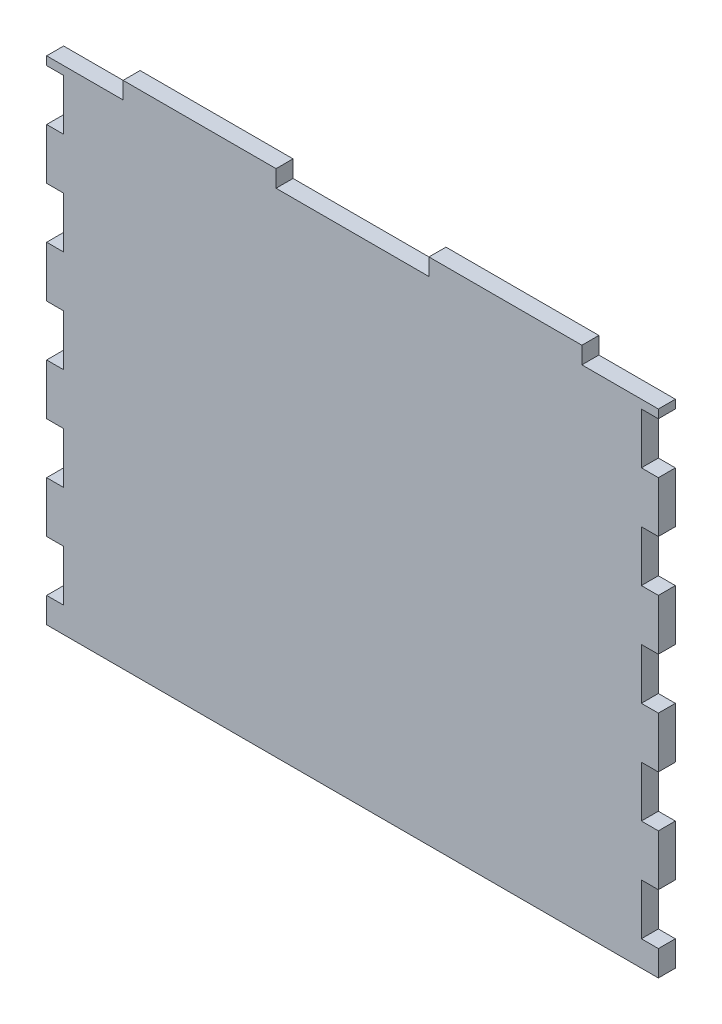
SolidWorks part; units mm, degrees
ref_plane "Front Plane" through (0, 0, 0) normal (0, 0, 1) x (1, 0, 0)
ref_plane "Top Plane" through (0, 0, 0) normal (0, 1, 0) x (1, 0, 0)
ref_plane "Right Plane" through (0, 0, 0) normal (1, 0, 0) x (0, 0, -1)
sketch "Sketch1" plane through (0, 0, 0) normal (0, 0, 1) x (1, 0, 0)
  line L0 (85.725, 100.551) -> (114.3, 100.551) construction
  line L1 (85.725, 95.25) -> (28.575, 95.25)
  line L2 (114.3, 88.9) -> (114.3, 85.725)
  line L3 (114.3, -95.25) -> (-114.3, -95.25)
  line L4 (-114.3, 88.9) -> (-114.3, 85.725)
  line L5 (114.3, 95.25) -> (-114.3, -95.25) construction
  line L6 (114.3, -95.25) -> (-114.3, 95.25) construction
  line L7 (85.725, 95.25) -> (85.725, 88.9)
  line L8 (28.575, 95.25) -> (28.575, 88.9)
  line L9 (-28.575, 95.25) -> (-28.575, 88.9)
  line L10 (-85.725, 95.25) -> (-85.725, 88.9)
  line L11 (-85.725, 88.9) -> (-114.3, 88.9)
  line L12 (-28.575, 88.9) -> (28.575, 88.9)
  line L13 (85.725, 88.9) -> (114.3, 88.9)
  line L14 (-28.575, 95.25) -> (-85.725, 95.25)
  line L15 (124.9833, 95.25) -> (124.9833, 85.725) construction
  line L16 (114.3, 85.725) -> (107.95, 85.725)
  line L17 (114.3, 66.675) -> (107.95, 66.675)
  line L18 (114.3, 47.625) -> (107.95, 47.625)
  line L19 (114.3, 28.575) -> (107.95, 28.575)
  line L20 (114.3, 9.525) -> (107.95, 9.525)
  line L21 (114.3, -9.525) -> (107.95, -9.525)
  line L22 (114.3, -28.575) -> (107.95, -28.575)
  line L23 (114.3, -47.625) -> (107.95, -47.625)
  line L24 (114.3, -66.675) -> (107.95, -66.675)
  line L25 (114.3, -85.725) -> (107.95, -85.725)
  line L26 (107.95, -9.525) -> (107.95, 9.525)
  line L27 (107.95, -85.725) -> (107.95, -66.675)
  line L28 (0, 49.4398) -> (0, -43.8374) construction
  line L29 (-114.3, -85.725) -> (-107.95, -85.725)
  line L30 (-114.3, -66.675) -> (-107.95, -66.675)
  line L31 (-114.3, -47.625) -> (-107.95, -47.625)
  line L32 (-114.3, -28.575) -> (-107.95, -28.575)
  line L33 (-114.3, -9.525) -> (-107.95, -9.525)
  line L34 (-114.3, 9.525) -> (-107.95, 9.525)
  line L35 (-114.3, 28.575) -> (-107.95, 28.575)
  line L36 (-114.3, 47.625) -> (-107.95, 47.625)
  line L37 (-114.3, 66.675) -> (-107.95, 66.675)
  line L38 (-114.3, 85.725) -> (-107.95, 85.725)
  line L39 (-107.95, -47.625) -> (-107.95, -28.575)
  line L40 (-114.3, 66.675) -> (-114.3, 47.625)
  line L41 (-114.3, 28.575) -> (-114.3, 9.525)
  line L42 (-114.3, -9.525) -> (-114.3, -28.575)
  line L43 (-114.3, -47.625) -> (-114.3, -66.675)
  line L44 (-114.3, -85.725) -> (-114.3, -95.25)
  line L45 (-107.95, -85.725) -> (-107.95, -66.675)
  line L46 (-107.95, -9.525) -> (-107.95, 9.525)
  line L47 (-107.95, 28.575) -> (-107.95, 47.625)
  line L48 (-107.95, 66.675) -> (-107.95, 85.725)
  line L49 (114.3, 66.675) -> (114.3, 47.625)
  line L50 (114.3, 28.575) -> (114.3, 9.525)
  line L51 (107.95, 66.675) -> (107.95, 85.725)
  line L52 (107.95, 28.575) -> (107.95, 47.625)
  line L53 (114.3, -9.525) -> (114.3, -28.575)
  line L54 (114.3, -47.625) -> (114.3, -66.675)
  line L55 (107.95, -47.625) -> (107.95, -28.575)
  line L56 (114.3, -85.725) -> (114.3, -95.25)
  point P0 (0, 0)
  dimension "D1" = 190.5
  dimension "D2" = 228.6
  dimension "D3" = 28.575
  dimension "D4" = 6.35
  dimension "D5" = 4
  dimension "D6" = 9.525
  dimension "D7" = 6.35
  dimension "D9" = 3.175
  dimension "D8" = 10
extrude "Boss-Extrude1" add sketch "Sketch1" along normal blind 6.35
sketch "Sketch2" plane through (0, 0, 0) normal (0, 0, -1) x (-1, 0, 0)
  line L0 (-114.3, 88.9) -> (114.3, 88.9)
  line L1 (-107.95, -66.675) -> (-104.775, -66.675)
  line L2 (-104.775, -66.675) -> (-104.775, -95.25)
  line L3 (114.3, -95.25) -> (-114.3, -95.25) construction
  line L4 (107.95, -66.675) -> (104.775, -66.675)
  line L5 (104.775, -66.675) -> (104.775, -95.25)
  dimension "D1" = 3.175
  dimension "D2" = 3.175
